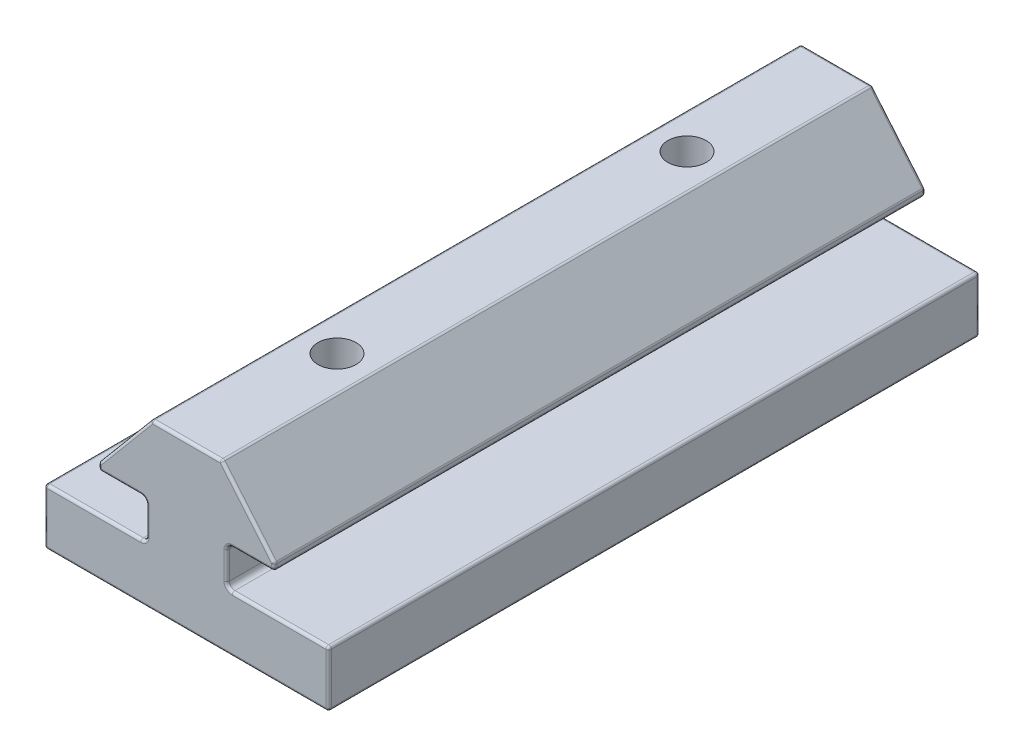
SolidWorks part; units mm, degrees
ref_plane "Front Plane" through (0, 0, 0) normal (0, 0, 1) x (1, 0, 0)
ref_plane "Top Plane" through (0, 0, 0) normal (0, 1, 0) x (1, 0, 0)
ref_plane "Right Plane" through (0, 0, 0) normal (1, 0, 0) x (0, 0, -1)
sketch "Sketch1" plane through (0, 0, 0) normal (0, 0, 1) x (1, 0, 0)
  line L0 (-2.921, -1.905) -> (-10.3124, -1.905) construction
  line L1 (-10.3124, -1.905) -> (-10.3124, -5.969) construction
  line L2 (-10.3124, -5.969) -> (10.3124, -5.969) construction
  line L3 (10.3124, -5.969) -> (10.3124, -1.905) construction
  line L4 (10.3124, -1.905) -> (2.921, -1.905) construction
  line L5 (2.921, -1.905) -> (2.921, 0.889) construction
  line L6 (2.921, 0.889) -> (6.3764, 0.889) construction
  line L7 (6.3764, 0.889) -> (6.3764, 1.397) construction
  line L8 (6.3764, 1.397) -> (2.54, 5.969) construction
  line L9 (2.54, 5.969) -> (-2.54, 5.969) construction
  line L10 (-2.54, 5.969) -> (-6.3764, 1.397) construction
  line L11 (-6.3764, 1.397) -> (-6.3764, 0.889) construction
  line L12 (-6.3764, 0.889) -> (-2.921, 0.889) construction
  line L13 (-2.921, 0.889) -> (-2.921, -1.905) construction
  line L14 (0, -5.969) -> (0, 5.969) construction
  line L15 (0, -38.1) -> (0, 38.1) construction
  point P16 (0, 12.7)
  point P19 (0, 0)
  point P21 (0, 0)
  point P22 (0, -12.7)
  dimension "Width" = 20.6248
  dimension "Top Width" = 5.08
  dimension "Angle Edge Height" = 0.508
  dimension "Slide Angle" = 50
  dimension "Base Thickness" = 4.064
  dimension "Middle Section Width" = 5.842
  dimension "Height" = 11.938
  dimension "For Rail Height 3" = 76.2
  dimension "For Rail Height 1" = 25.4
  dimension "For Rail Height 2" = 50.8
  dimension "Notch Height" = 2.794
sketch "Sketch2" plane through (0, 0, 0) normal (0, 1, 0) x (1, 0, 0)
  line L0 (0, -23.622) -> (0, 23.622) construction
  line L2 (0, 0) -> (10.287, 0) construction
  line L3 (-10.3124, 0) -> (10.3124, 0) construction
  line L4 (10.3124, 0) -> (2.921, 0) construction
  circle A0 centre (0, -12.7) radius 1.3843 construction
  circle A1 centre (0, 12.7) radius 1.3843 construction
  point P3 (-6.35, -23.622)
  point P4 (0, 0)
  dimension "Mounting Hole Dia." = 2.7686
  dimension "Length" = 47.244
  dimension "Mounting Hole Spacing" = 25.4
  dimension "Hole Edge Offset" = 10.3124
  dimension "Hole End Offset" = 10.922
  dimension "Slide Offset" = 3.9624
sketch "Sketch3" plane through (0, 0, 0) normal (0, 0, 1) x (1, 0, 0)
  line L0 (-6.3764, 1.397) -> (-6.3764, 0.889) construction
  line L1 (-6.3764, 0.889) -> (-2.921, 0.889) construction
  line L2 (-2.921, 0.889) -> (-2.921, -1.905) construction
  line L3 (-2.921, -1.905) -> (-10.3124, -1.905) construction
  line L4 (-10.3124, -1.905) -> (-10.3124, -5.969) construction
  line L5 (-10.3124, -5.969) -> (10.3124, -5.969) construction
  line L6 (10.3124, -5.969) -> (10.3124, -1.905) construction
  line L7 (10.3124, -1.905) -> (2.921, -1.905) construction
  line L8 (2.921, -1.905) -> (2.921, 0.889) construction
  line L9 (6.3764, 0.889) -> (6.3764, 1.397) construction
  line L10 (2.921, 0.889) -> (6.3764, 0.889) construction
  line L11 (6.3764, 1.397) -> (2.54, 5.969) construction
  line L12 (2.54, 5.969) -> (-2.54, 5.969) construction
  line L13 (-2.54, 5.969) -> (-6.3764, 1.397) construction
  line L14 (-6.3764, 1.397) -> (-6.3764, 0.889)
  line L15 (-6.3764, 0.889) -> (-2.921, 0.889)
  line L16 (-2.921, 0.889) -> (-2.921, -1.905)
  line L17 (-2.921, -1.905) -> (-10.3124, -1.905)
  line L18 (-10.3124, -1.905) -> (-10.3124, -5.969)
  line L19 (-10.3124, -5.969) -> (10.3124, -5.969)
  line L20 (10.3124, -5.969) -> (10.3124, -1.905)
  line L21 (10.3124, -1.905) -> (2.921, -1.905)
  line L22 (2.921, -1.905) -> (2.921, 0.889)
  line L23 (6.3764, 0.889) -> (6.3764, 1.397)
  line L24 (2.921, 0.889) -> (6.3764, 0.889)
  line L25 (6.3764, 1.397) -> (2.54, 5.969)
  line L26 (2.54, 5.969) -> (-2.54, 5.969)
  line L27 (-2.54, 5.969) -> (-6.3764, 1.397)
extrude "Boss-Extrude1" add sketch "Sketch3" along normal mid plane 47.244
sketch "Sketch5" plane through (0, -5.969, 0) normal (0, -1, 0) x (1, 0, 0)
  circle A0 centre (0, 12.7) radius 1.3843 construction
  circle A1 centre (0, -12.7) radius 1.3843 construction
  circle A2 centre (0, 12.7) radius 1.3843
  circle A3 centre (0, -12.7) radius 1.3843
extrude "Cut-Extrude1" cut sketch "Sketch5" against normal through all
fillet "Fillet1" radius 0.3969 4 edges at (-2.921, -1.905, 0) (2.921, -1.905, 0) (2.921, 0.889, 0) (-2.921, 0.889, 0)
fillet "Fillet2" radius 0.1984 46 edges at (-10.3124, -5.969, 0) (10.3124, -5.969, 0) (-6.3764, 1.143, -23.622) (-4.8471, 0.889, -23.622) (-3.0372, 0.7728, -23.622) (-2.921, -0.508, -23.622) (-3.0372, -1.7888, -23.622) (-6.8151, -1.905, -23.622) (-10.3124, -3.937, -23.622) (0, -5.969, -23.622) (10.3124, -3.937, -23.622) (6.8151, -1.905, -23.622) (3.0372, -1.7888, -23.622) (2.921, -0.508, -23.622) (3.0372, 0.7728, -23.622) (4.8471, 0.889, -23.622) (6.3764, 1.143, -23.622) (4.4582, 3.683, -23.622) (0, 5.969, -23.622) (-4.4582, 3.683, -23.622) (0, 5.969, 23.622) (4.4582, 3.683, 23.622) (6.3764, 1.143, 23.622) (4.8471, 0.889, 23.622) (3.0372, 0.7728, 23.622) (2.921, -0.508, 23.622) (3.0372, -1.7888, 23.622) (6.8151, -1.905, 23.622) (10.3124, -3.937, 23.622) (0, -5.969, 23.622) (-10.3124, -3.937, 23.622) (-6.8151, -1.905, 23.622) (-3.0372, -1.7888, 23.622) (-2.921, -0.508, 23.622) (-3.0372, 0.7728, 23.622) (-4.8471, 0.889, 23.622) (-6.3764, 1.143, 23.622) (-4.4582, 3.683, 23.622) (-10.3124, -1.905, 0) (10.3124, -1.905, 0) (-2.54, 5.969, 0) (2.54, 5.969, 0) (6.3764, 0.889, 0) (6.3764, 1.397, 0) (-6.3764, 0.889, 0) (-6.3764, 1.397, 0)
equation "\"D1@Boss-Extrude1\"=\"Length@Sketch2\""
